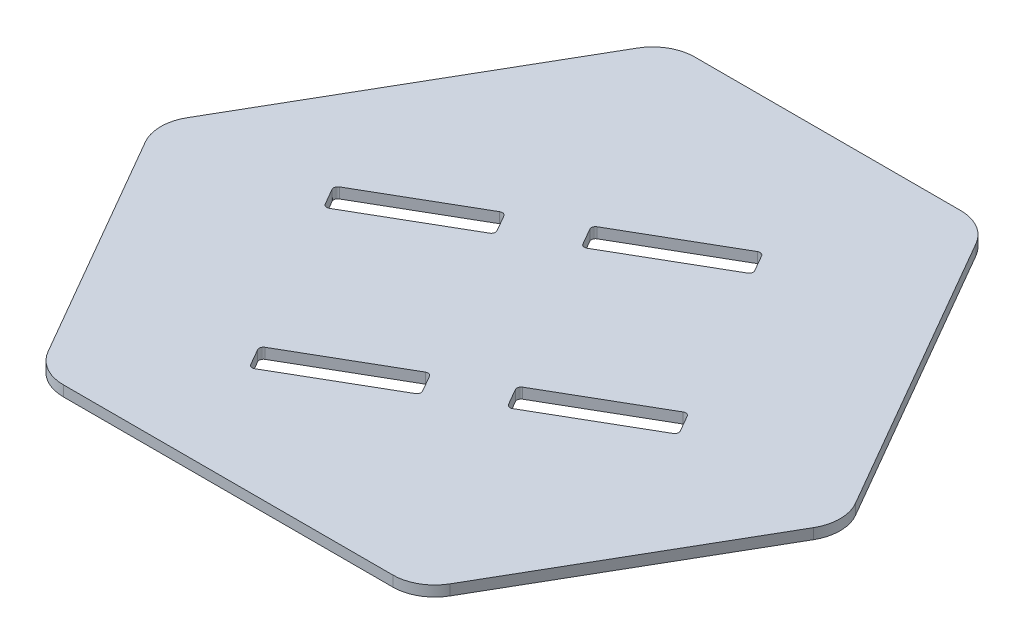
SolidWorks part; units mm, degrees
ref_plane "前基準面" through (0, 0, 0) normal (0, 0, 1) x (1, 0, 0)
ref_plane "上基準面" through (0, 0, 0) normal (0, 1, 0) x (1, 0, 0)
ref_plane "右基準面" through (0, 0, 0) normal (1, 0, 0) x (0, 0, -1)
sketch "草圖1" plane through (0, 0, 0) normal (0, 1, 0) x (1, 0, 0)
  line L0 (-90.1222, 0) -> (90.1222, 0)
  line L1 (90.1222, 0) -> (165.1222, 129.9038)
  line L2 (165.1222, 129.9038) -> (75, 286)
  line L3 (75, 286) -> (-75, 286)
  line L4 (-75, 286) -> (-165.1222, 129.9038)
  line L5 (-165.1222, 129.9038) -> (-90.1222, 0)
  dimension "D1" = 286
  dimension "D2" = 286
  dimension "D3" = 286
  dimension "D4" = 150
  dimension "D5" = 60
extrude "填料-伸長1" add sketch "草圖1" along normal blind 5
fillet "圓角1" radius 20 6 edges at (90.1222, 2.5, 0) (-90.1222, 2.5, 0) (-165.1222, 2.5, -129.9038) (-75, 2.5, -286) (75, 2.5, -286) (165.1222, 2.5, -129.9038)
sketch "草圖2" plane through (0, 5, 0) normal (0, 1, 0) x (1, 0, 0)
  line L0 (-127.6222, 64.9519) -> (120.0611, 207.9519) construction
  line L1 (-3.7805, 136.4519) -> (-127.2101, 350.2382) construction
  line L2 (-159.3487, 119.9038) -> (-95.8957, 10) construction
  line L3 (-11.7902, 180.325) -> (40.1714, 210.325)
  line L4 (40.1714, 210.325) -> (33.6714, 221.5833)
  line L5 (33.6714, 221.5833) -> (-18.2902, 191.5833)
  line L6 (-18.2902, 191.5833) -> (-11.7902, 180.325)
  line L7 (-44.2709, 176.5833) -> (-37.7709, 165.325)
  line L8 (-96.2324, 146.5833) -> (-44.2709, 176.5833)
  line L9 (-89.7324, 135.325) -> (-96.2324, 146.5833)
  line L10 (-37.7709, 165.325) -> (-89.7324, 135.325)
  line L11 (4.2291, 92.5788) -> (-47.7324, 62.5788)
  line L12 (-47.7324, 62.5788) -> (-41.2324, 51.3205)
  line L13 (-41.2324, 51.3205) -> (10.7291, 81.3205)
  line L14 (10.7291, 81.3205) -> (4.2291, 92.5788)
  line L15 (36.7098, 96.3205) -> (30.2098, 107.5788)
  line L16 (88.6714, 126.3205) -> (36.7098, 96.3205)
  line L17 (82.1714, 137.5788) -> (88.6714, 126.3205)
  line L18 (30.2098, 107.5788) -> (82.1714, 137.5788)
  line L19 (159.3487, 139.9038) -> (80.7735, 276) construction
  dimension "D1" = 13
  dimension "D2" = 150
  dimension "D3" = 110
  dimension "D4" = 60
extrude "除料-伸長1" cut sketch "草圖2" against normal blind 10
fillet "圓角2" radius 2 16 edges at (88.6714, 2.5, -126.3205) (36.7098, 2.5, -96.3205) (30.2098, 2.5, -107.5788) (82.1714, 2.5, -137.5788) (-41.2324, 2.5, -51.3205) (10.7291, 2.5, -81.3205) (4.2291, 2.5, -92.5788) (-47.7324, 2.5, -62.5788) (33.6714, 2.5, -221.5833) (-18.2902, 2.5, -191.5833) (40.1714, 2.5, -210.325) (-11.7902, 2.5, -180.325) (-37.7709, 2.5, -165.325) (-89.7324, 2.5, -135.325) (-96.2324, 2.5, -146.5833) (-44.2709, 2.5, -176.5833)
